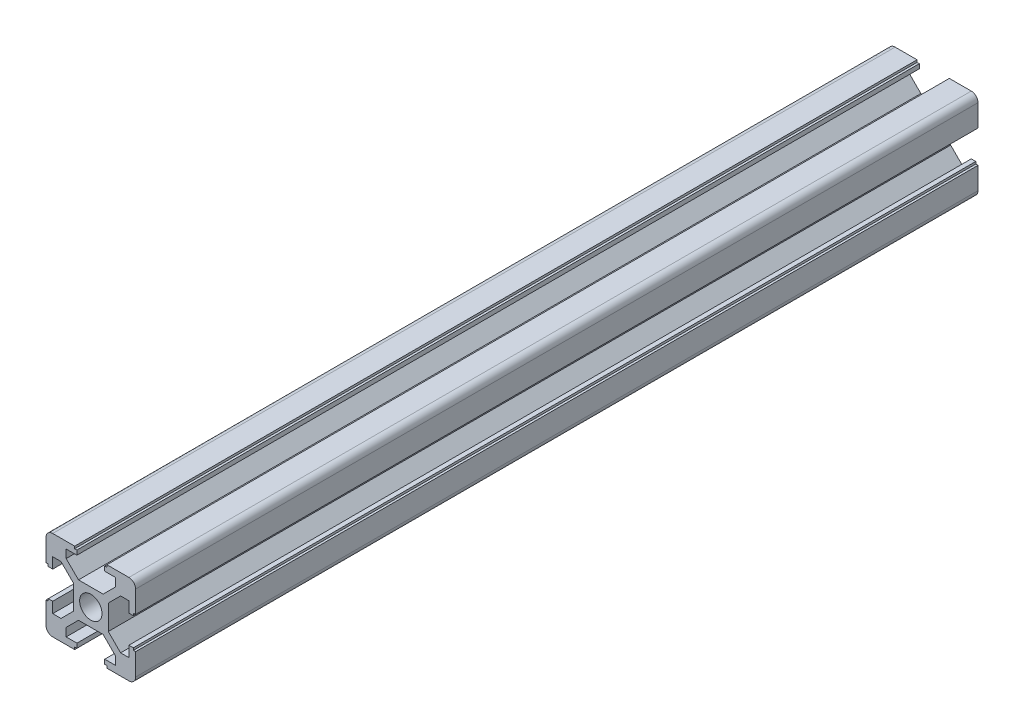
SolidWorks part; units mm, degrees
ref_plane "Plane1" through (0, 0, 0) normal (0, 0, 1) x (1, 0, 0)
ref_plane "Plane2" through (0, 0, 0) normal (0, 1, 0) x (1, 0, 0)
ref_plane "Plane3" through (0, 0, 0) normal (1, 0, 0) x (0, 0, -1)
sketch "Sketch1" plane through (0, 0, 0) normal (0, 0, 1) x (1, 0, 0)
  line L0 (-3.6, 10) -> (-3.6, 9.5)
  line L1 (-3.6, 9.5) -> (-3.1, 9.5)
  line L2 (-3.1, 9.5) -> (-3.1, 8.5)
  line L3 (-3.1, 8.5) -> (-5.5, 8.5)
  line L4 (-8.5, -10) -> (-3.6, -10)
  line L5 (-10, -8.5) -> (-10, -3.6)
  line L6 (8.5, 10) -> (3.6, 10)
  line L7 (10, 8.5) -> (10, 3.6)
  line L8 (0, 14.8756) -> (0, 0) construction
  line L9 (0, 0) -> (14.1675, 0) construction
  line L10 (-5.5, 8.5) -> (-5.5, 6.65)
  line L11 (-5.5, 6.65) -> (-2.75, 3.9)
  line L12 (-2.75, 3.9) -> (2.75, 3.9)
  line L13 (5.5, 6.65) -> (2.75, 3.9)
  line L14 (5.5, 8.5) -> (5.5, 6.65)
  line L15 (3.1, 8.5) -> (5.5, 8.5)
  line L16 (3.1, 9.5) -> (3.1, 8.5)
  line L17 (3.6, 9.5) -> (3.1, 9.5)
  line L18 (3.6, 10) -> (3.6, 9.5)
  line L19 (-3.6, 10) -> (-8.5, 10)
  line L20 (10, 3.6) -> (9.5, 3.6)
  line L21 (9.5, 3.6) -> (9.5, 3.1)
  line L22 (9.5, 3.1) -> (8.5, 3.1)
  line L23 (8.5, 3.1) -> (8.5, 5.5)
  line L24 (8.5, 5.5) -> (6.65, 5.5)
  line L25 (6.65, 5.5) -> (3.9, 2.75)
  line L26 (3.9, 2.75) -> (3.9, -2.75)
  line L27 (6.65, -5.5) -> (3.9, -2.75)
  line L28 (8.5, -5.5) -> (6.65, -5.5)
  line L29 (8.5, -3.1) -> (8.5, -5.5)
  line L30 (9.5, -3.1) -> (8.5, -3.1)
  line L31 (9.5, -3.6) -> (9.5, -3.1)
  line L32 (10, -3.6) -> (9.5, -3.6)
  line L33 (3.6, -10) -> (3.6, -9.5)
  line L34 (3.6, -9.5) -> (3.1, -9.5)
  line L35 (3.1, -9.5) -> (3.1, -8.5)
  line L36 (3.1, -8.5) -> (5.5, -8.5)
  line L37 (5.5, -8.5) -> (5.5, -6.65)
  line L38 (5.5, -6.65) -> (2.75, -3.9)
  line L39 (2.75, -3.9) -> (-2.75, -3.9)
  line L40 (-5.5, -6.65) -> (-2.75, -3.9)
  line L41 (-5.5, -8.5) -> (-5.5, -6.65)
  line L42 (-3.1, -8.5) -> (-5.5, -8.5)
  line L43 (-3.1, -9.5) -> (-3.1, -8.5)
  line L44 (-3.6, -9.5) -> (-3.1, -9.5)
  line L45 (-3.6, -10) -> (-3.6, -9.5)
  line L46 (-10, -3.6) -> (-9.5, -3.6)
  line L47 (-9.5, -3.6) -> (-9.5, -3.1)
  line L48 (-9.5, -3.1) -> (-8.5, -3.1)
  line L49 (-8.5, -3.1) -> (-8.5, -5.5)
  line L50 (-8.5, -5.5) -> (-6.65, -5.5)
  line L51 (-6.65, -5.5) -> (-3.9, -2.75)
  line L52 (-3.9, -2.75) -> (-3.9, 2.75)
  line L53 (-6.65, 5.5) -> (-3.9, 2.75)
  line L54 (-8.5, 5.5) -> (-6.65, 5.5)
  line L55 (-8.5, 3.1) -> (-8.5, 5.5)
  line L56 (-9.5, 3.1) -> (-8.5, 3.1)
  line L57 (-9.5, 3.6) -> (-9.5, 3.1)
  line L58 (-10, 3.6) -> (-9.5, 3.6)
  line L59 (3.6, -10) -> (8.5, -10)
  line L60 (-10, 3.6) -> (-10, 8.5)
  line L61 (10, -3.6) -> (10, -8.5)
  circle A0 centre (0, 0) radius 2.5
  arc A1 (-10, 8.5) -> (-8.5, 10) centre (-8.5, 8.5) cw
  arc A2 (10, 8.5) -> (8.5, 10) centre (8.5, 8.5) ccw
  arc A3 (-8.5, -10) -> (-10, -8.5) centre (-8.5, -8.5) cw
  arc A4 (8.5, -10) -> (10, -8.5) centre (8.5, -8.5) ccw
  point P0 (-10, 0)
  point P1 (10, 0)
  point P2 (0, 10)
  point P3 (0, -10)
  point P4 (0, 0)
  point P5 (-10, -10)
  point P6 (10, -10)
  point P7 (10, 10)
  point P8 (-10, 10)
  point P36 (-10, 10)
  point P39 (10, 10)
extrude "凸台-拉伸1" add sketch "Sketch1" along normal blind 188
sketch "草图1" plane through (0, 3.9, 0) normal (0, 1, 0) x (1, 0, 0)
  line L0 (2.75, 0) -> (-2.75, 0) construction
  line L2 (2.75, -188) -> (-2.75, -188) construction
  circle A0 centre (0, -32) radius 2.2
  circle A1 centre (0, -56) radius 2.2
  circle A3 centre (0, -106) radius 2.2
  circle A4 centre (0, -132) radius 2.2
  circle A5 centre (0, -156) radius 2.2
  circle A6 centre (0, -82) radius 2.2
  point P0 (0, -32)
  point P3 (0, -56)
  point P6 (0, -82)
  point P9 (0, -106)
  point P10 (0, -132)
  point P11 (0, -156)
  dimension "D2" = 24
  dimension "D3" = 26
  dimension "D5" = 26
  dimension "D7" = 32
  dimension "D1" = 32
  dimension "D4" = 24
  dimension "D6" = 24
extrude "切除-拉伸1" cut sketch "草图1" against normal through all
